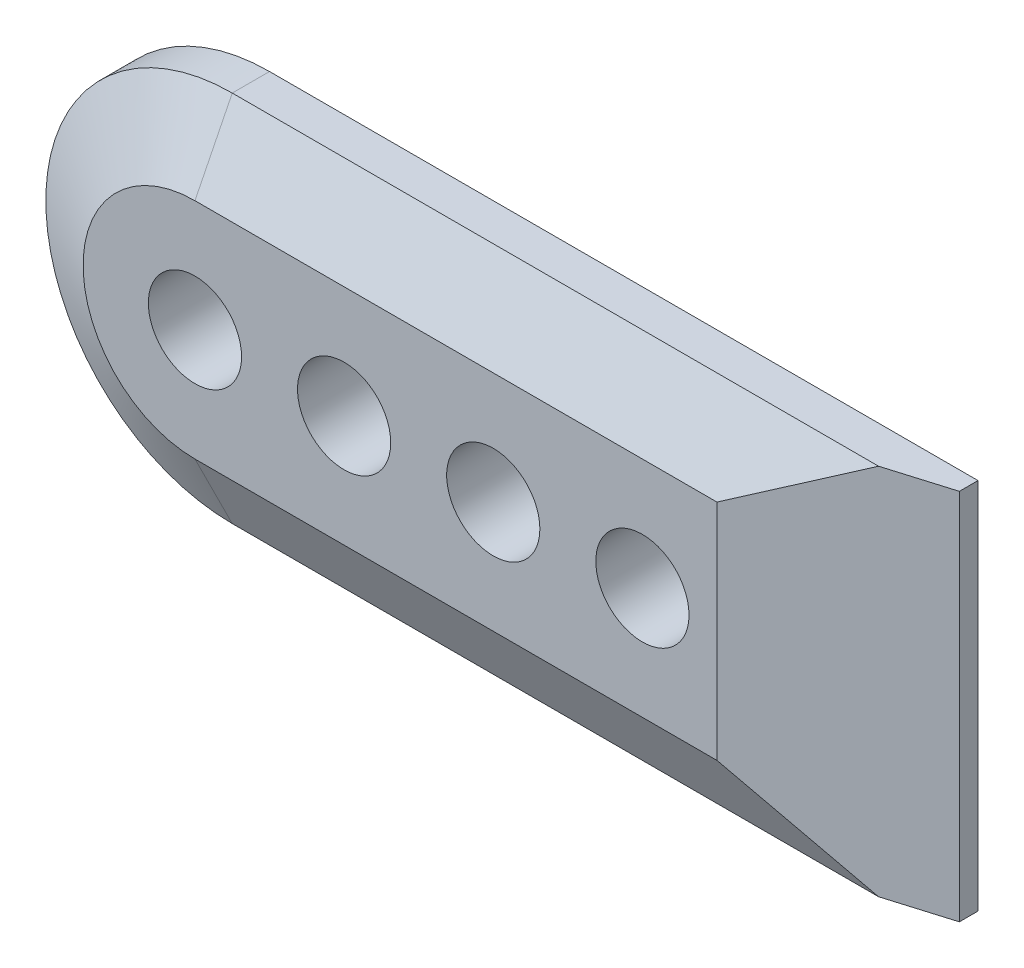
SolidWorks part; units mm, degrees
ref_plane "Front Plane" through (0, 0, 0) normal (0, 0, 1) x (1, 0, 0)
ref_plane "Top Plane" through (0, 0, 0) normal (0, 1, 0) x (1, 0, 0)
ref_plane "Right Plane" through (0, 0, 0) normal (1, 0, 0) x (0, 0, -1)
sketch "Sketch2" plane through (0, 0, 0) normal (0, 0, 1) x (1, 0, 0)
  line L1 (0, 2500) -> (4750, 2500)
  line L3 (0, 0) -> (4750, 0)
  line L4 (4750, 2500) -> (4750, 0)
  arc A0 (0, 2500) -> (0, 0) centre (0, 1250) ccw
  point P6 (1408.0687, 2065.7547)
  point P7 (0, 0)
  point P8 (219.2791, 2490.3648)
  dimension "D3" = 1250
  dimension "D1" = 4750
  dimension "D2" = 2500
extrude "Boss-Extrude1" add sketch "Sketch2" along normal blind 500
chamfer "Chamfer1" distance 250 distance2 500 3 edges at (2375, 2500, 500) (2375, 0, 500) (-1250, 1250, 500)
chamfer "Chamfer2" distance 375 distance2 1250 1 edges at (4750, 1250, 500)
sketch "Sketch3" plane through (0, 0, 500) normal (0, 0, 1) x (1, 0, 0)
  circle A0 centre (0, 1250) radius 312.5
  arc A3 (0, 2000) -> (0, 500) centre (0, 1250) ccw construction
  circle A4 centre (1000, 1250) radius 312.5
  circle A5 centre (2000, 1250) radius 312.5
  circle A6 centre (3000, 1250) radius 312.5
  point P2 (0, 0)
  point P3 (1006.1077, 1250)
  dimension "D1" = 625
  dimension "D2" = 4
  dimension "D3" = 1000
extrude "Cut-Extrude1" cut sketch "Sketch3" against normal through all contours A6 | A5 | A4 | A0
